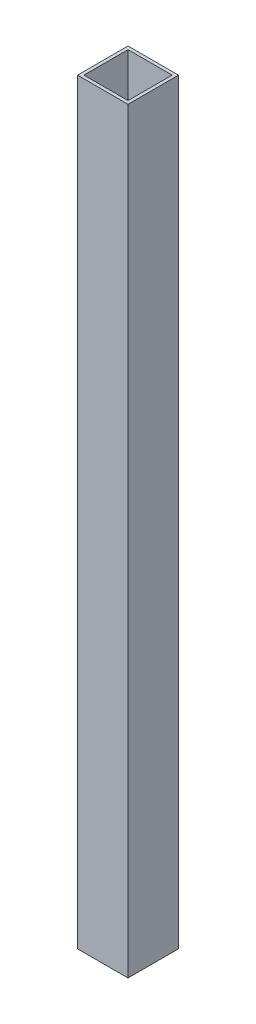
SolidWorks part; units mm, degrees
ref_plane "Front Plane" through (0, 0, 0) normal (0, 0, 1) x (1, 0, 0)
ref_plane "Top Plane" through (0, 0, 0) normal (0, 1, 0) x (1, 0, 0)
ref_plane "Right Plane" through (0, 0, 0) normal (1, 0, 0) x (0, 0, -1)
sketch "Sketch1" plane through (0, 0, 0) normal (0, 1, 0) x (1, 0, 0)
  line L1 (-12.7, -12.7) -> (12.7, -12.7)
  line L2 (-12.7, -12.7) -> (-12.7, 12.7)
  line L3 (-12.7, 12.7) -> (12.7, 12.7)
  line L4 (12.7, -12.7) -> (12.7, 12.7)
  line L5 (-12.7, -12.7) -> (12.7, 12.7) construction
  line L6 (-12.7, 12.7) -> (12.7, -12.7) construction
  line L7 (-11.1125, -11.1125) -> (11.1125, -11.1125)
  line L8 (-11.1125, -11.1125) -> (-11.1125, 11.1125)
  line L9 (-11.1125, 11.1125) -> (11.1125, 11.1125)
  line L10 (11.1125, -11.1125) -> (11.1125, 11.1125)
  line L11 (-11.1125, -11.1125) -> (11.1125, 11.1125) construction
  line L12 (-11.1125, 11.1125) -> (11.1125, -11.1125) construction
  point P0 (0, 0)
  point P6 (0, 0)
  dimension "D1" = 25.4
  dimension "D2" = 1.5875
extrude "Boss-Extrude1" add sketch "Sketch1" along normal blind 381
